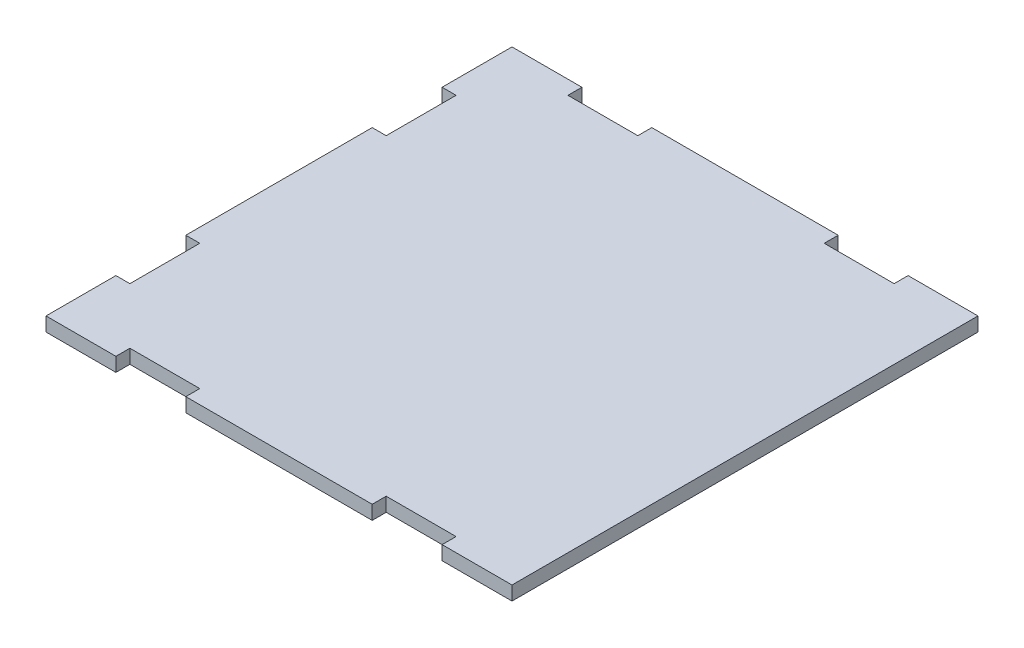
SolidWorks part; units mm, degrees
ref_plane "Plano frontal" through (0, 0, 0) normal (0, 0, 1) x (1, 0, 0)
ref_plane "Plano superior" through (0, 0, 0) normal (0, 1, 0) x (1, 0, 0)
ref_plane "Plano direito" through (0, 0, 0) normal (1, 0, 0) x (0, 0, -1)
sketch "Esboço1" plane through (0, 0, 0) normal (0, 1, 0) x (1, 0, 0)
  line L1 (-100, -100) -> (100, -100)
  line L2 (-100, -100) -> (-100, 100)
  line L3 (-100, 100) -> (100, 100)
  line L4 (100, -100) -> (100, 100)
  line L5 (-100, -100) -> (100, 100) construction
  line L6 (-100, 100) -> (100, -100) construction
  point P0 (0, 0)
  dimension "D1" = 200
  dimension "D2" = 200
extrude "Ressalto-extrusão1" add sketch "Esboço1" along normal blind 6
sketch "Esboço2" plane through (0, 6, 0) normal (0, 1, 0) x (1, 0, 0)
  line L0 (-100, -100) -> (100, -100) construction
  line L1 (-70, -100) -> (-40, -100)
  line L2 (-70, -100) -> (-70, -94)
  line L3 (-70, -94) -> (-40, -94)
  line L4 (-40, -100) -> (-40, -94)
  line L5 (100, -100) -> (100, 100) construction
  line L6 (40, -100) -> (70, -100)
  line L7 (40, -100) -> (40, -94)
  line L8 (40, -94) -> (70, -94)
  line L9 (70, -100) -> (70, -94)
  line L10 (-100, 100) -> (-100, -100) construction
  line L11 (100, 100) -> (-100, 100) construction
  line L12 (-70, 100) -> (-40, 100)
  line L13 (-70, 100) -> (-70, 94)
  line L14 (-70, 94) -> (-40, 94)
  line L15 (-40, 100) -> (-40, 94)
  line L17 (40, 100) -> (70, 100)
  line L18 (40, 100) -> (40, 94)
  line L19 (40, 94) -> (70, 94)
  line L20 (70, 100) -> (70, 94)
  line L21 (-100, 70) -> (-94, 70)
  line L22 (-100, 70) -> (-100, 40)
  line L23 (-100, 40) -> (-94, 40)
  line L24 (-94, 70) -> (-94, 40)
  line L25 (-100, -40) -> (-94, -40)
  line L26 (-100, -40) -> (-100, -70)
  line L27 (-100, -70) -> (-94, -70)
  line L28 (-94, -40) -> (-94, -70)
  point P10 (70, -97)
  dimension "D1" = 30
  dimension "D2" = 30
  dimension "D3" = 6
  dimension "D4" = 6
  dimension "D5" = 30
  dimension "D6" = 30
  dimension "D7" = 30
  dimension "D8" = 30
  dimension "D9" = 30
  dimension "D10" = 6
  dimension "D11" = 30
  dimension "D12" = 6
  dimension "D13" = 6
  dimension "D14" = 6
  dimension "D15" = 30
  dimension "D16" = 30
  dimension "D17" = 30
  dimension "D18" = 30
extrude "Corte-extrusão1" cut sketch "Esboço2" against normal blind 10
